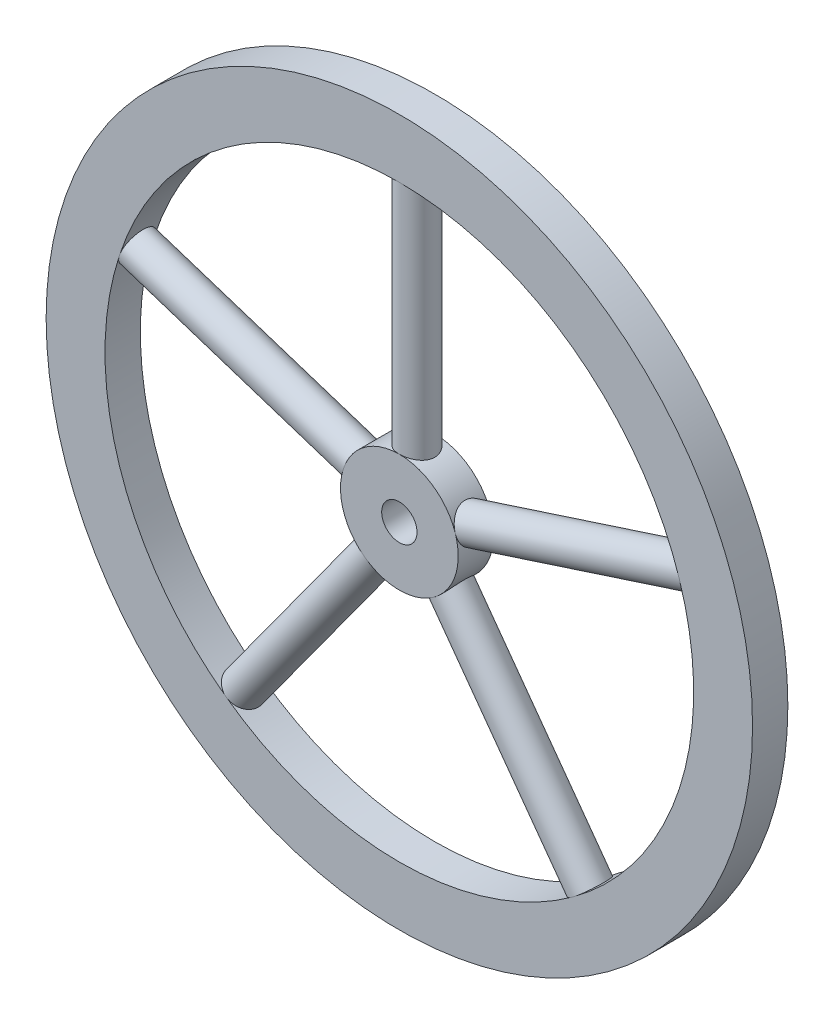
SolidWorks part; units mm, degrees
ref_plane "Front Plane" through (0, 0, 0) normal (0, 0, 1) x (1, 0, 0)
ref_plane "Top Plane" through (0, 0, 0) normal (0, 1, 0) x (1, 0, 0)
ref_plane "Right Plane" through (0, 0, 0) normal (1, 0, 0) x (0, 0, -1)
sketch "Sketch1" plane through (0, 0, 0) normal (0, 0, 1) x (1, 0, 0)
  circle A0 centre (0, 0) radius 300
  circle A2 centre (0, 0) radius 250
  circle A3 centre (0, 0) radius 50
  circle A4 centre (0, 0) radius 15
  dimension "D1" = 600
  dimension "D2" = 500
  dimension "D3" = 100
  dimension "D4" = 30
extrude "Boss-Extrude1" add sketch "Sketch1" along normal mid plane 30 contours A0 A2 | A3 A4
sketch "Sketch2" plane through (0, 0, 0) normal (0, 0, 1) x (1, 0, 0)
  line L0 (0, 0) -> (0, 277.3087) construction
  line L2 (0, 15) -> (15, 15)
  line L3 (0, 15) -> (0, 265)
  line L4 (0, 265) -> (15, 265)
  line L5 (15, 15) -> (15, 265)
  circle A0 centre (0, 0) radius 15 construction
  dimension "D1" = 250
  dimension "D2" = 15
revolve "Revolve1" add sketch "Sketch2" angle 360 about L0
pattern_circular "CirPattern1" count 5 over 360 about axis through (0, 0, 15) along (0, 0, -1) of "Revolve1"
